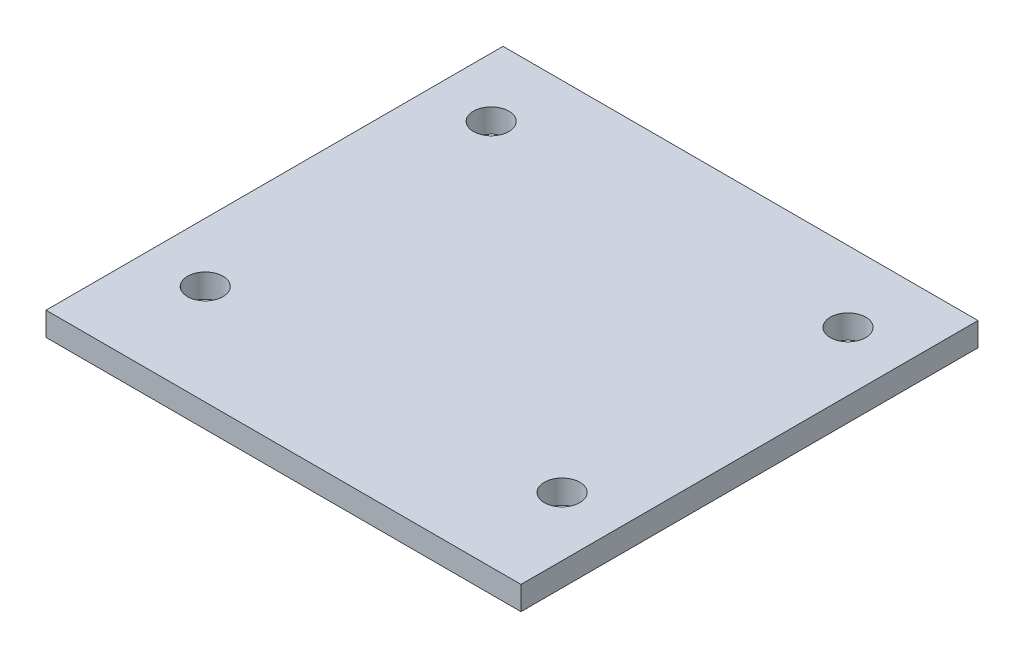
SolidWorks part; units mm, degrees
ref_plane "Front Plane" through (0, 0, 0) normal (0, 0, 1) x (1, 0, 0)
ref_plane "Top Plane" through (0, 0, 0) normal (0, 1, 0) x (1, 0, 0)
ref_plane "Right Plane" through (0, 0, 0) normal (1, 0, 0) x (0, 0, -1)
sketch "Sketch1" plane through (0, 0, 0) normal (0, 1, 0) x (1, 0, 0)
  line L0 (-20.1, -19.3394) -> (20.1, -19.3394)
  line L1 (20.1, -19.3394) -> (20.1, 19.3394)
  line L2 (20.1, 19.3394) -> (-20.1, 19.3394)
  line L3 (-20.1, 19.3394) -> (-20.1, -19.3394)
  circle A0 centre (-15.1, 13.3394) radius 1.5
  circle A1 centre (15.1, 13.3394) radius 1.5
  circle A2 centre (15.1, -10.8606) radius 1.5
  circle A3 centre (-15.1, -10.8606) radius 1.5
extrude "Boss-Extrude1" add sketch "Sketch1" along normal blind 2
